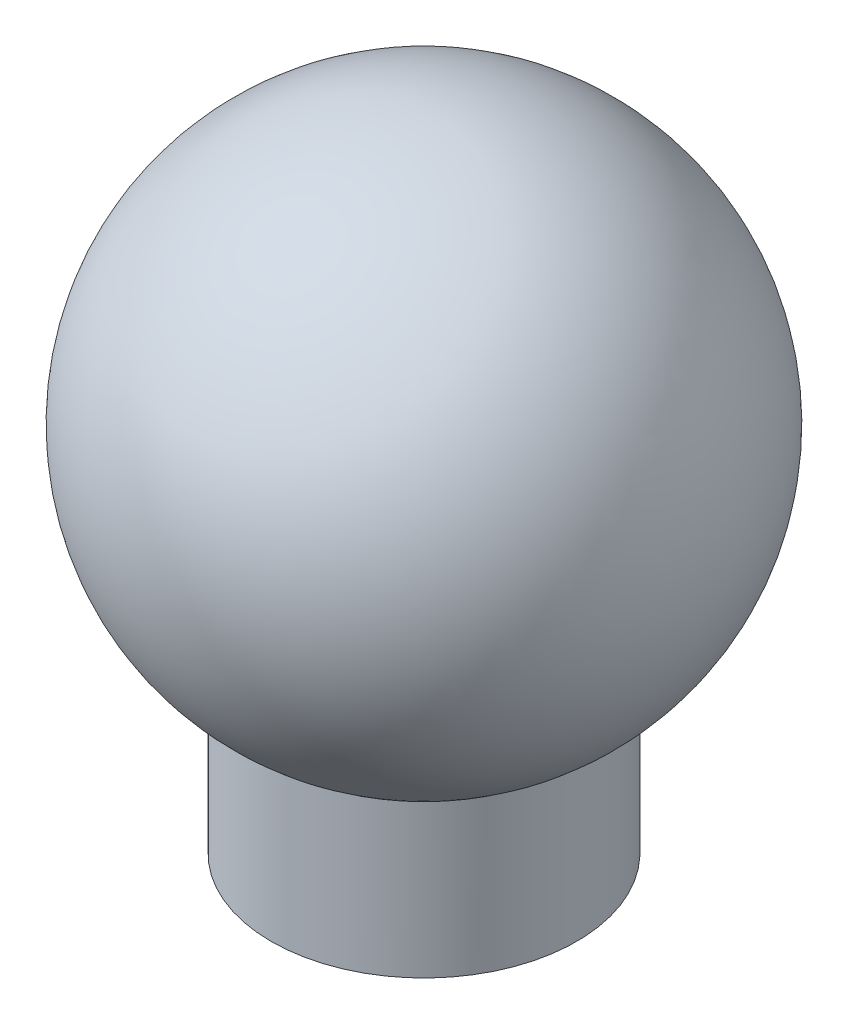
SolidWorks part; units mm, degrees
material "AISI 4340 Steel, normalized"
ref_plane "Front Plane" through (0, 0, 0) normal (0, 0, 1) x (1, 0, 0)
ref_plane "Top Plane" through (0, 0, 0) normal (0, 1, 0) x (1, 0, 0)
ref_plane "Right Plane" through (0, 0, 0) normal (1, 0, 0) x (0, 0, -1)
sketch "Sketch1" plane through (0, 0, 0) normal (0, 1, 0) x (1, 0, 0)
  circle A0 centre (0, 0) radius 25.4
  dimension "D1" = 50.8
extrude "Boss-Extrude1" add sketch "Sketch1" along normal blind 25.4
sketch "Sketch2" plane through (0, 0, 0) normal (0, 0, 1) x (1, 0, 0)
  line L0 (0, 145.4603) -> (0, 25.4)
  line L1 (25.4, 25.4) -> (-25.4, 25.4) construction
  line L2 (0, 25.4) -> (25.4, 25.4)
  line L3 (25.4, 0) -> (25.4, 25.4) construction
  circle A0 centre (0, 61.878) radius 44.45
  dimension "D1" = 88.9
revolve "Revolve1" add sketch "Sketch2" angle 360 about L0
ref_plane "Plane1" [suppressed] through (0, 58.42, 0) normal (0, 1, 0) x (1, 0, 0)
sketch "Sketch3" [suppressed] plane through (0, 58.42, 0) normal (0, 1, 0) x (1, 0, 0)
  line L1 (-57.15, 57.15) -> (57.15, 57.15)
  line L2 (-57.15, 57.15) -> (-57.15, -57.15)
  line L3 (-57.15, -57.15) -> (57.15, -57.15)
  line L4 (57.15, 57.15) -> (57.15, -57.15)
  circle A0 centre (0, 0) radius 44.45 construction
  point P5 (0, -57.15)
  point P7 (57.15, 0)
  point P10 (0, 44.45)
  point P11 (44.45, 0)
  dimension "D1" = 12.7
  dimension "D2" = 12.7
extrude "Boss-Extrude2" [suppressed] add sketch "Sketch3" along normal blind 50.8
fillet "Fillet1" [suppressed] radius 25.4
sketch "Sketch4" plane through (0, 0, 0) normal (0, -1, 0) x (1, 0, 0)
  point P0 (0, 0)
